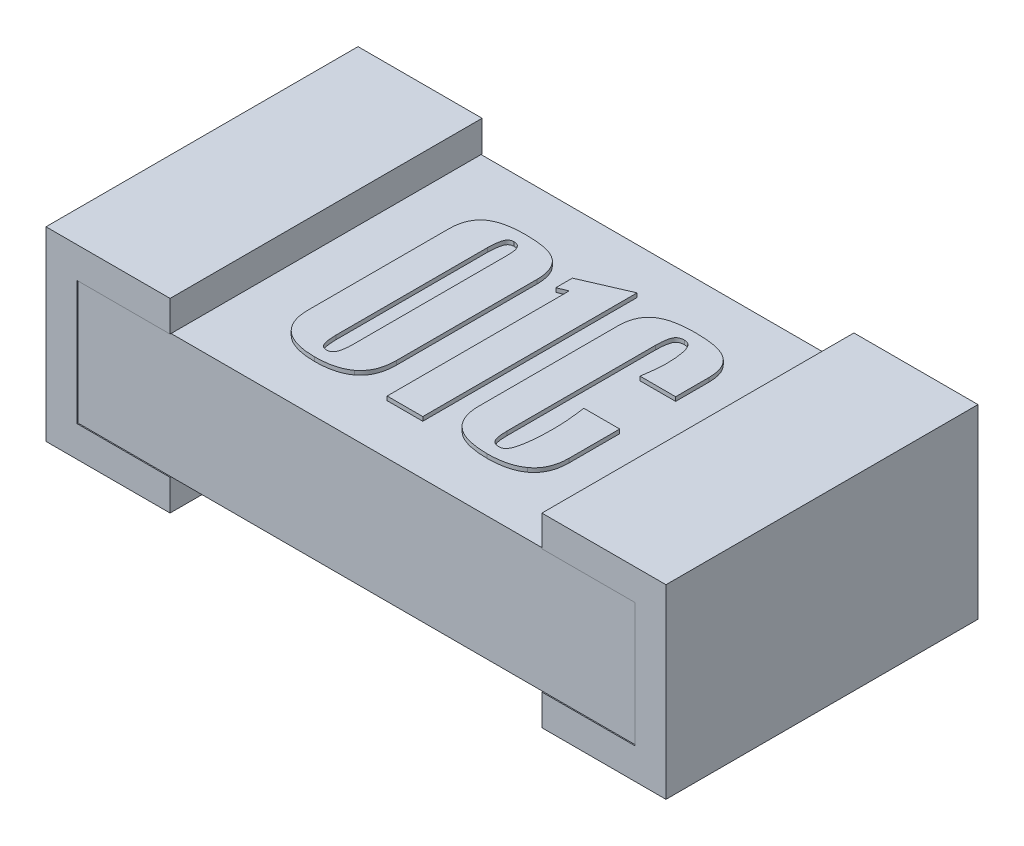
SolidWorks part; units mm, degrees
ref_plane "Plano frontal" through (0, 0, 0) normal (0, 0, 1) x (1, 0, 0)
ref_plane "Plano superior" through (0, 0, 0) normal (0, 1, 0) x (1, 0, 0)
ref_plane "Plano direito" through (0, 0, 0) normal (1, 0, 0) x (0, 0, -1)
sketch "Esboço1" plane through (0, 0, 0) normal (0, 0, 1) x (1, 0, 0)
  line L1 (-0.686, -0.1525) -> (0.686, -0.1525)
  line L2 (-0.686, -0.1525) -> (-0.686, 0.1525)
  line L3 (-0.686, 0.1525) -> (0.686, 0.1525)
  line L4 (0.686, -0.1525) -> (0.686, 0.1525)
  line L5 (-0.686, -0.1525) -> (0.686, 0.1525) construction
  line L6 (-0.686, 0.1525) -> (0.686, -0.1525) construction
  point P0 (0, 0)
  dimension "D1" = 1.372
  dimension "D2" = 0.305
extrude "Ressalto-extrusão1" add sketch "Esboço1" along normal mid plane 0.762
sketch "Esboço2" plane through (0, 0, 0) normal (0, 0, 1) x (1, 0, 0)
  line L0 (-0.457, 0.1525) -> (-0.686, 0.1525)
  line L1 (0.686, 0.1525) -> (-0.686, 0.1525) construction
  line L2 (-0.686, 0.1525) -> (-0.686, -0.1525)
  line L3 (-0.686, -0.1525) -> (-0.457, -0.1525)
  line L4 (-0.686, -0.1525) -> (0.686, -0.1525) construction
  line L5 (-0.457, -0.1525) -> (-0.457, -0.2285)
  line L6 (-0.457, -0.2285) -> (-0.762, -0.2285)
  line L7 (-0.762, -0.2285) -> (-0.762, 0.2285)
  line L8 (-0.762, 0.2285) -> (-0.457, 0.2285)
  line L9 (-0.457, 0.2285) -> (-0.457, 0.1525)
  dimension "D1" = 0.076
  dimension "D2" = 0.076
  dimension "D3" = 0.076
  dimension "D4" = 0.305
  dimension "D5" = 0.305
extrude "Ressalto-extrusão2" add sketch "Esboço2" along normal mid plane 0.767
mirror "Espelhar1" about plane through (0, 0, 0) normal (1, 0, 0) of "Ressalto-extrusão2"
sketch "Sketch1" plane through (0, 0.1525, 0) normal (0, 1, 0) x (1, 0, 0)
  text T0 "01C" font "DESIREE" height in points 2
extrude "Boss-Extrude1" add sketch "Sketch1" along normal blind 0.01
